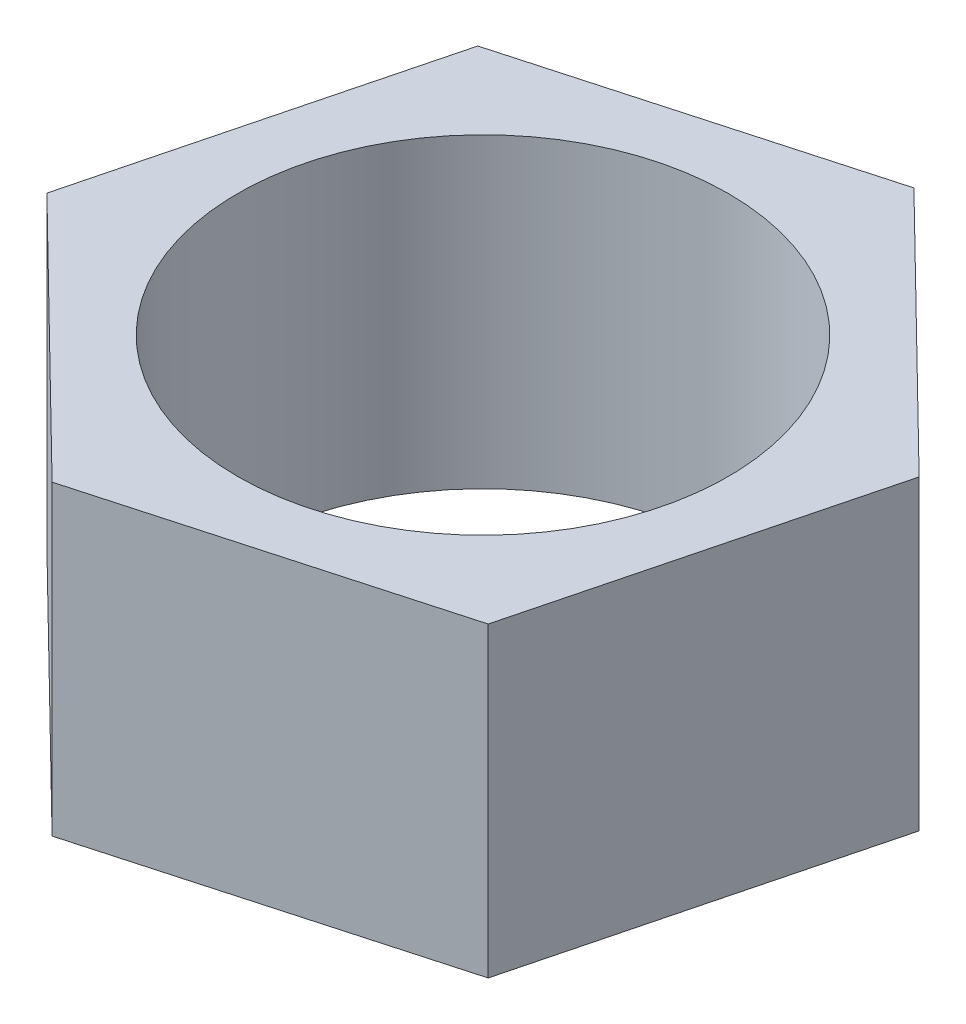
SolidWorks part; units mm, degrees
ref_plane "Front Plane" through (0, 0, 0) normal (0, 0, 1) x (1, 0, 0)
ref_plane "Top Plane" through (0, 0, 0) normal (0, 1, 0) x (1, 0, 0)
ref_plane "Right Plane" through (0, 0, 0) normal (1, 0, 0) x (0, 0, -1)
sketch "Sketch1" plane through (0, 0, 0) normal (0, 1, 0) x (1, 0, 0)
  line L1 (4.1248, -4.0397) -> (5.5609, 1.5523)
  line L2 (5.5609, 1.5523) -> (1.4361, 5.592)
  line L3 (1.4361, 5.592) -> (-4.1248, 4.0397)
  line L4 (-4.1248, 4.0397) -> (-5.5609, -1.5523)
  line L5 (-5.5609, -1.5523) -> (-1.4361, -5.592)
  line L6 (-1.4361, -5.592) -> (4.1248, -4.0397)
  circle A0 centre (0, 0) radius 4
  circle A1 centre (0, 0) radius 5 construction
  dimension "D1" = 8
  dimension "D2" = 10
extrude "Boss-Extrude1" add sketch "Sketch1" along normal blind 5
